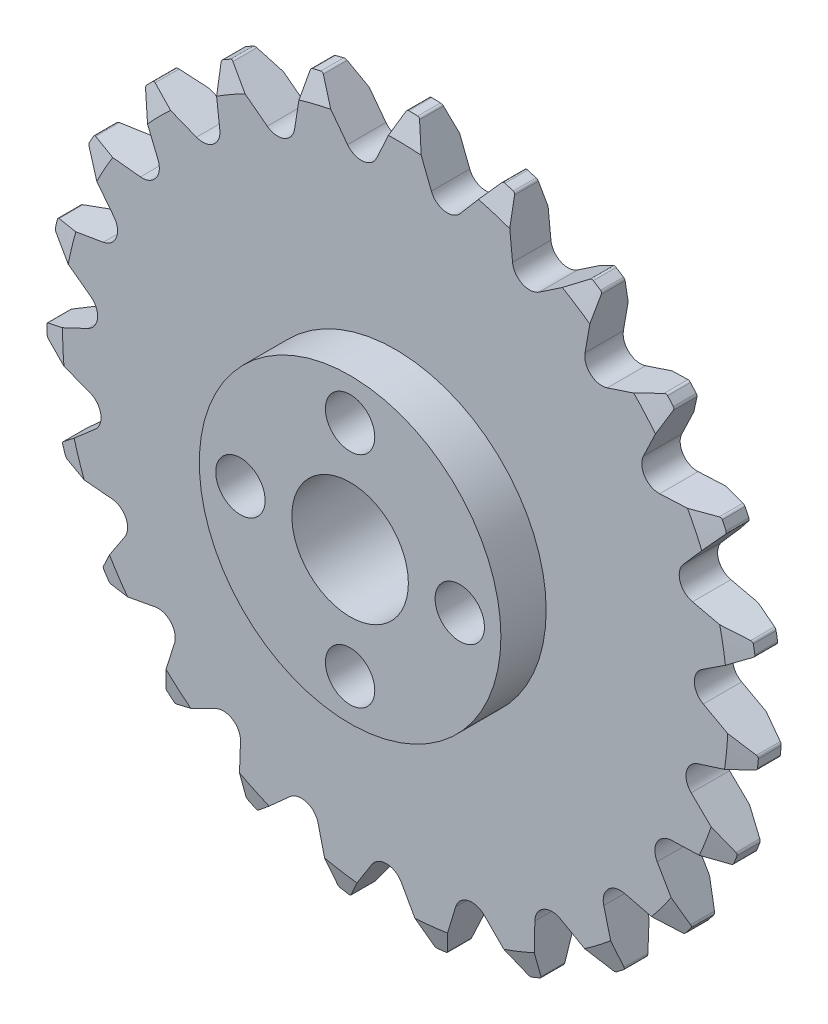
SolidWorks part; units mm, degrees
material "2024 Alloy"
ref_plane "Front Plane" through (0, 0, 0) normal (0, 0, 1) x (1, 0, 0)
ref_plane "Top Plane" through (0, 0, 0) normal (0, 1, 0) x (1, 0, 0)
ref_plane "Right Plane" through (0, 0, 0) normal (1, 0, 0) x (0, 0, -1)
sketch "Sketch1" plane through (0, 0, 0) normal (0, 1, 0) x (1, 0, 0)
  line L0 (26, 2.8) -> (0, 2.8)
  line L1 (0, 2.8) -> (0, 0)
  line L2 (0, 0) -> (26, 0)
  line L3 (26, 0) -> (26, 2.8)
  line L4 (0, 2.8) -> (0, 0) construction
revolve "Revolve1" add sketch "Sketch1" angle 360 about L4
sketch "Sketch2" plane through (0, 0, -2.8) normal (0, 0, -1) x (-1, 0, 0)
  line L0 (18.8013, 17.9586) -> (17.3085, 14.3114)
  line L1 (18.595, 12.5946) -> (22.5146, 13.0035)
  arc A0 (22.5146, 13.0035) -> (18.8013, 17.9586) centre (0, 0) ccw
  arc A1 (17.3085, 14.3114) -> (18.595, 12.5946) centre (18.4653, 13.8379) ccw
extrude "Cut-Extrude1" cut sketch "Sketch2" against normal through all
sketch "Sketch3" plane through (0, 0, -2.8) normal (0, 0, -1) x (-1, 0, 0)
  line L0 (22.9493, 12.2201) -> (20.5278, 9.1109)
  line L1 (21.3035, 7.1107) -> (25.188, 6.4469)
  arc A0 (25.188, 6.4469) -> (22.9493, 12.2201) centre (0, 0) ccw
  arc A1 (20.5278, 9.1109) -> (21.3035, 7.1107) centre (21.514, 8.3429) ccw
extrude "Cut-Extrude2" cut sketch "Sketch3" against normal through all
sketch "Sketch4" plane through (0, 0, -2.8) normal (0, 0, -1) x (-1, 0, 0)
  line L0 (25.3952, 5.5753) -> (22.2247, 3.2347)
  line L1 (22.4319, 1.0994) -> (25.9934, -0.5878)
  arc A0 (25.9934, -0.5878) -> (25.3952, 5.5753) centre (0, 0) ccw
  arc A1 (22.2247, 3.2347) -> (22.4319, 1.0994) centre (22.9671, 2.2291) ccw
extrude "Cut-Extrude3" cut sketch "Sketch4" against normal through all
sketch "Sketch5" plane through (0, 0, -2.8) normal (0, 0, -1) x (-1, 0, 0)
  line L0 (25.9577, -1.483) -> (22.2732, -2.8814)
  line L1 (21.8967, -4.9934) -> (24.8709, -7.5789)
  arc A0 (24.8709, -7.5789) -> (25.9577, -1.483) centre (0, 0) ccw
  arc A1 (22.2732, -2.8814) -> (21.8967, -4.9934) centre (22.7168, -4.05) ccw
extrude "Cut-Extrude4" cut sketch "Sketch5" against normal through all
sketch "Sketch6" plane through (0, 0, -2.8) normal (0, 0, -1) x (-1, 0, 0)
  line L0 (24.595, -8.4313) -> (20.6699, -8.7838)
  line L1 (19.7375, -10.7159) -> (21.9038, -14.0079)
  arc A0 (21.9038, -14.0079) -> (24.595, -8.4313) centre (0, 0) ccw
  arc A1 (20.6699, -8.7838) -> (19.7375, -10.7159) centre (20.7817, -10.0288) ccw
extrude "Cut-Extrude5" cut sketch "Sketch6" against normal through all
sketch "Sketch7" plane through (0, 0, -2.8) normal (0, 0, -1) x (-1, 0, 0)
  line L0 (21.4082, -14.7543) -> (17.5336, -14.0347)
  line L1 (16.1145, -15.6436) -> (17.3123, -19.3981)
  arc A0 (17.3123, -19.3981) -> (21.4082, -14.7543) centre (0, 0) ccw
  arc A1 (17.5336, -14.0347) -> (16.1145, -15.6436) centre (17.3053, -15.2637) ccw
extrude "Cut-Extrude6" cut sketch "Sketch7" against normal through all
sketch "Sketch8" plane through (0, 0, -2.8) normal (0, 0, -1) x (-1, 0, 0)
  line L0 (16.6337, -19.983) -> (13.0969, -18.2448)
  line L1 (11.2963, -19.4112) -> (11.4367, -23.3495)
  arc A0 (11.4367, -23.3495) -> (16.6337, -19.983) centre (0, 0) ccw
  arc A1 (13.0969, -18.2448) -> (11.2963, -19.4112) centre (12.5455, -19.3666) ccw
extrude "Cut-Extrude7" cut sketch "Sketch8" against normal through all
sketch "Sketch9" plane through (0, 0, -2.8) normal (0, 0, -1) x (-1, 0, 0)
  line L0 (10.6255, -23.7297) -> (7.6888, -21.1017)
  line L1 (5.6403, -21.7391) -> (4.713, -25.5693)
  arc A0 (4.713, -25.5693) -> (10.6255, -23.7297) centre (0, 0) ccw
  arc A1 (7.6888, -21.1017) -> (5.6403, -21.7391) centre (6.8552, -22.0332) ccw
extrude "Cut-Extrude8" cut sketch "Sketch9" against normal through all
sketch "Sketch10" plane through (0, 0, -2.8) normal (0, 0, -1) x (-1, 0, 0)
  line L0 (3.8293, -25.7165) -> (1.7105, -22.3936)
  line L1 (-0.4339, -22.4547) -> (-2.3603, -25.8926)
  arc A0 (-2.3603, -25.8926) -> (3.8293, -25.7165) centre (0, 0) ccw
  arc A1 (1.7105, -22.3936) -> (-0.4339, -22.4547) centre (0.6565, -23.0657) ccw
extrude "Cut-Extrude9" cut sketch "Sketch10" against normal through all
sketch "Sketch11" plane through (0, 0, -2.8) normal (0, 0, -1) x (-1, 0, 0)
  line L0 (-3.2509, -25.796) -> (-4.3946, -22.0247)
  line L1 (-6.476, -21.5049) -> (-9.2585, -24.2957)
  arc A0 (-9.2585, -24.2957) -> (-3.2509, -25.796) centre (0, 0) ccw
  arc A1 (-4.3946, -22.0247) -> (-6.476, -21.5049) centre (-5.5908, -22.3875) ccw
extrude "Cut-Extrude10" cut sketch "Sketch11" against normal through all
sketch "Sketch12" plane through (0, 0, -2.8) normal (0, 0, -1) x (-1, 0, 0)
  line L0 (-10.0901, -23.9623) -> (-10.1739, -20.0223)
  line L1 (-12.0379, -18.9602) -> (-15.4701, -20.8968)
  arc A0 (-15.4701, -20.8968) -> (-10.0901, -23.9623) centre (0, 0) ccw
  arc A1 (-10.1739, -20.0223) -> (-12.0379, -18.9602) centre (-11.4236, -20.0489) ccw
extrude "Cut-Extrude11" cut sketch "Sketch12" against normal through all
sketch "Sketch13" plane through (0, 0, -2.8) normal (0, 0, -1) x (-1, 0, 0)
  line L0 (-16.1808, -20.3514) -> (-15.1985, -16.5349)
  line L1 (-16.7069, -15.0093) -> (-20.5343, -15.9481)
  arc A0 (-20.5343, -15.9481) -> (-16.1808, -20.3514) centre (0, 0) ccw
  arc A1 (-15.1985, -16.5349) -> (-16.7069, -15.0093) centre (-16.4091, -16.2234) ccw
extrude "Cut-Extrude12" cut sketch "Sketch13" against normal through all
sketch "Sketch14" plane through (0, 0, -2.8) normal (0, 0, -1) x (-1, 0, 0)
  line L0 (-21.0716, -15.2312) -> (-19.096, -11.8213)
  line L1 (-20.1368, -9.9453) -> (-24.0756, -9.8167)
  arc A0 (-24.0756, -9.8167) -> (-21.0716, -15.2312) centre (0, 0) ccw
  arc A1 (-19.096, -11.8213) -> (-20.1368, -9.9453) centre (-20.1776, -11.1946) ccw
extrude "Cut-Extrude13" cut sketch "Sketch14" against normal through all
sketch "Sketch15" plane through (0, 0, -2.8) normal (0, 0, -1) x (-1, 0, 0)
  line L0 (-24.3995, -8.9813) -> (-21.5772, -6.2309)
  line L1 (-22.0733, -4.1437) -> (-25.8313, -2.9571)
  arc A0 (-25.8313, -2.9571) -> (-24.3995, -8.9813) centre (0, 0) ccw
  arc A1 (-21.5772, -6.2309) -> (-22.0733, -4.1437) centre (-22.4496, -5.3357) ccw
extrude "Cut-Extrude14" cut sketch "Sketch15" against normal through all
sketch "Sketch16" plane through (0, 0, -2.8) normal (0, 0, -1) x (-1, 0, 0)
  line L0 (-25.9178, -2.0654) -> (-22.4581, -0.1783)
  line L1 (-22.3727, 1.9653) -> (-25.6712, 4.1217)
  arc A0 (-25.6712, 4.1217) -> (-25.9178, -2.0654) centre (0, 0) ccw
  arc A1 (-22.4581, -0.1783) -> (-22.3727, 1.9653) centre (-23.0567, 0.919) ccw
extrude "Cut-Extrude15" cut sketch "Sketch16" against normal through all
sketch "Sketch17" plane through (0, 0, -2.8) normal (0, 0, -1) x (-1, 0, 0)
  line L0 (-25.514, 5.0037) -> (-21.6734, 5.8874)
  line L1 (-21.0128, 7.9285) -> (-23.6072, 10.8949)
  arc A0 (-23.6072, 10.8949) -> (-25.514, 5.0037) centre (0, 0) ccw
  arc A1 (-21.6734, 5.8874) -> (-21.0128, 7.9285) centre (-21.9537, 7.1056) ccw
extrude "Cut-Extrude16" cut sketch "Sketch17" against normal through all
sketch "Sketch18" plane through (0, 0, -2.8) normal (0, 0, -1) x (-1, 0, 0)
  line L0 (-23.2178, 11.7018) -> (-19.2813, 11.5165)
  line L1 (-18.0945, 13.3037) -> (-19.7924, 16.86)
  arc A0 (-19.7924, 16.86) -> (-23.2178, 11.7018) centre (0, 0) ccw
  arc A1 (-19.2813, 11.5165) -> (-18.0945, 13.3037) centre (-19.2226, 12.7651) ccw
extrude "Cut-Extrude17" cut sketch "Sketch18" against normal through all
sketch "Sketch19" plane through (0, 0, -2.8) normal (0, 0, -1) x (-1, 0, 0)
  line L0 (-19.1998, 17.5319) -> (-15.4592, 16.2915)
  line L1 (-13.8342, 17.6922) -> (-14.5097, 21.5748)
  arc A0 (-14.5097, 21.5748) -> (-19.1998, 17.5319) centre (0, 0) ccw
  arc A1 (-15.4592, 16.2915) -> (-13.8342, 17.6922) centre (-15.0657, 17.478) ccw
extrude "Cut-Extrude18" cut sketch "Sketch19" against normal through all
sketch "Sketch20" plane through (0, 0, -2.8) normal (0, 0, -1) x (-1, 0, 0)
  line L0 (-13.7577, 22.0618) -> (-10.4905, 19.8582)
  line L1 (-8.5479, 20.7685) -> (-8.1508, 24.6894)
  arc A0 (-8.1508, 24.6894) -> (-13.7577, 22.0618) centre (0, 0) ccw
  arc A1 (-10.4905, 19.8582) -> (-8.5479, 20.7685) centre (-9.7916, 20.8945) ccw
extrude "Cut-Extrude19" cut sketch "Sketch20" against normal through all
sketch "Sketch21" plane through (0, 0, -2.8) normal (0, 0, -1) x (-1, 0, 0)
  line L0 (-7.2953, 24.9555) -> (-4.7438, 21.9521)
  line L1 (-2.6277, 22.3046) -> (-1.1874, 25.9729)
  arc A0 (-1.1874, 25.9729) -> (-7.2953, 24.9555) centre (0, 0) ccw
  arc A1 (-4.7438, 21.9521) -> (-2.6277, 22.3046) centre (-3.7912, 22.7614) ccw
extrude "Cut-Extrude20" cut sketch "Sketch21" against normal through all
sketch "Sketch22" plane through (0, 0, -2.8) normal (0, 0, -1) x (-1, 0, 0)
  line L0 (-0.2919, 25.9984) -> (1.3547, 22.418)
  line L1 (3.4875, 22.1864) -> (5.864, 25.3301)
  arc A0 (5.864, 25.3301) -> (-0.2919, 25.9984) centre (0, 0) ccw
  arc A1 (1.3547, 22.418) -> (3.4875, 22.1864) centre (2.4903, 22.9402) ccw
extrude "Cut-Extrude21" cut sketch "Sketch22" against normal through all
sketch "Sketch23" plane through (0, 0, -2.8) normal (0, 0, -1) x (-1, 0, 0)
  line L0 (6.7332, 25.113) -> (7.3527, 21.2211)
  line L1 (9.344, 20.4228) -> (12.4805, 22.8087)
  arc A0 (12.4805, 22.8087) -> (6.7332, 25.113) centre (0, 0) ccw
  arc A1 (7.3527, 21.2211) -> (9.344, 20.4228) centre (8.5872, 21.4176) ccw
extrude "Cut-Extrude22" cut sketch "Sketch23" against normal through all
sketch "Sketch24" plane through (0, 0, -2.8) normal (0, 0, -1) x (-1, 0, 0)
  line L0 (13.2589, 22.3652) -> (12.8055, 18.4505)
  line L1 (14.5075, 17.1445) -> (18.1714, 18.5957)
  arc A0 (18.1714, 18.5957) -> (13.2589, 22.3652) centre (0, 0) ccw
  arc A1 (12.8055, 18.4505) -> (14.5075, 17.1445) centre (14.0472, 18.3066) ccw
extrude "Cut-Extrude23" cut sketch "Sketch24" against normal through all
sketch "Sketch25" plane through (0, 0, 0) normal (0, 1, 0) x (1, 0, 0)
  line L0 (11, 0) -> (0, 0)
  line L1 (0, 0) -> (0, -3.302)
  line L2 (0, -3.302) -> (11, -3.302)
  line L3 (11, -3.302) -> (11, 0)
  line L4 (0, 0) -> (0, -3.302) construction
revolve "Revolve2" add sketch "Sketch25" angle 360 about L4
hole_wizard "Ø8.0 (8) Diameter Hole1" positions "Sketch27" profile "Sketch26" hole size "Ø8.0" standard "ANSI Metric"
sketch "Sketch27" plane through (0, 0, 3.302) normal (0, 0, 1) x (1, 0, 0)
  point P0 (0, 0)
sketch "Sketch26" plane through (0, 0, 3.302) normal (1, 0, 0) x (0, -1, 0)
  line L0 (0, 0) -> (0, 6.102)
  line L1 (0, 6.102) -> (4.25, 6.102)
  line L2 (4.25, 6.102) -> (4.25, 0)
  line L5 (4.25, 0) -> (0, 0)
  line L11 (0, -6.35) -> (0, 107.95) construction
  dimension "Thru Hole Dia." = 8.5
  dimension "Thru Hole Depth" = 6.102
hole_wizard "Ø3.6 (3.6) Diameter Hole1" positions "Sketch29" profile "Sketch28" hole size "Ø3.6" standard "ANSI Metric"
sketch "Sketch29" plane through (0, 0, 3.302) normal (0, 0, 1) x (1, 0, 0)
  point P0 (0, 8)
  point P1 (-8, 0)
  point P2 (0, -8)
sketch "Sketch28" plane through (0, 8, 3.302) normal (1, 0, 0) x (0, -1, 0)
  line L0 (0, 0) -> (0, 6.102)
  line L1 (0, 6.102) -> (1.8, 6.102)
  line L2 (1.8, 6.102) -> (1.8, 0)
  line L5 (1.8, 0) -> (0, 0)
  line L11 (0, -6.35) -> (0, 107.95) construction
  dimension "Thru Hole Dia." = 3.6
  dimension "Thru Hole Depth" = 6.102
hole_wizard "Ø3.6 (3.6) Diameter Hole2" positions "Sketch31" profile "Sketch30" hole size "Ø3.6" standard "ANSI Metric"
sketch "Sketch31" plane through (0, 0, -2.8) normal (0, 0, -1) x (-1, 0, 0)
  point P0 (-8, 0)
sketch "Sketch30" plane through (8, 0, -2.8) normal (1, 0, 0) x (0, 1, 0)
  line L0 (0, 0) -> (0, 6.102)
  line L1 (0, 6.102) -> (1.8, 6.102)
  line L2 (1.8, 6.102) -> (1.8, 0)
  line L5 (1.8, 0) -> (0, 0)
  line L11 (0, -6.35) -> (0, 107.95) construction
  dimension "Thru Hole Dia." = 3.6
  dimension "Thru Hole Depth" = 6.102
fillet "Fillet1" radius 0.2 46 edges at (25.8313, -2.9571, -1.4) (25.9178, -2.0654, -1.4) (9.2585, -24.2957, -1.4) (10.0901, -23.9623, -1.4) (14.5097, 21.5748, -1.4) (13.7577, 22.0618, -1.4) (-13.2589, 22.3652, -1.4) (-12.4805, 22.8087, -1.4) (20.5343, -15.9481, -1.4) (21.0716, -15.2312, -1.4) (-18.8013, 17.9586, -1.4) (-18.1714, 18.5957, -1.4) (23.6072, 10.8949, -1.4) (23.2178, 11.7018, -1.4) (1.1874, 25.9729, -1.4) (0.2919, 25.9984, -1.4) (-22.9493, 12.2201, -1.4) (-22.5146, 13.0035, -1.4) (15.4701, -20.8968, -1.4) (16.1808, -20.3514, -1.4) (24.0756, -9.8167, -1.4) (24.3995, -8.9813, -1.4) (-25.3952, 5.5753, -1.4) (-25.188, 6.4469, -1.4) (25.6712, 4.1217, -1.4) (25.514, 5.0037, -1.4) (19.7924, 16.86, -1.4) (19.1998, 17.5319, -1.4) (-25.9577, -1.483, -1.4) (-25.9934, -0.5878, -1.4) (8.1508, 24.6894, -1.4) (7.2953, 24.9555, -1.4) (-5.864, 25.3301, -1.4) (-6.7332, 25.113, -1.4) (-24.595, -8.4313, -1.4) (-24.8709, -7.5789, -1.4) (-21.4082, -14.7543, -1.4) (-21.9038, -14.0079, -1.4) (-16.6337, -19.983, -1.4) (-17.3123, -19.3981, -1.4) (-10.6255, -23.7297, -1.4) (-11.4367, -23.3495, -1.4) (-3.8293, -25.7165, -1.4) (-4.713, -25.5693, -1.4) (3.2509, -25.796, -1.4) (2.3603, -25.8926, -1.4)
sketch "Sketch32" plane through (0, 0, 0) normal (1, 0, 0) x (0, 0, -1)
  line L0 (0, 24.2697) -> (0, 26.0477)
  line L1 (0, 26.0477) -> (0.5842, 26.0477)
  line L2 (0.5842, 26.0477) -> (0, 24.2697)
  line L3 (1.4, 25.8518) -> (1.4, 8.3868) construction
  line L4 (2.8, 25.8518) -> (0, 25.8518) construction
  line L5 (0, 0) -> (13.057, 0) construction
  line L6 (2.2158, 26.0477) -> (2.8, 24.2697)
  line L7 (2.8, 26.0477) -> (2.2158, 26.0477)
  line L8 (2.8, 24.2697) -> (2.8, 26.0477)
  dimension "D1" = 24.2697
  dimension "D2" = 1.778
  dimension "D3" = 0.5842
revolve "Cut-Revolve1" cut sketch "Sketch32" angle 360 about L5
